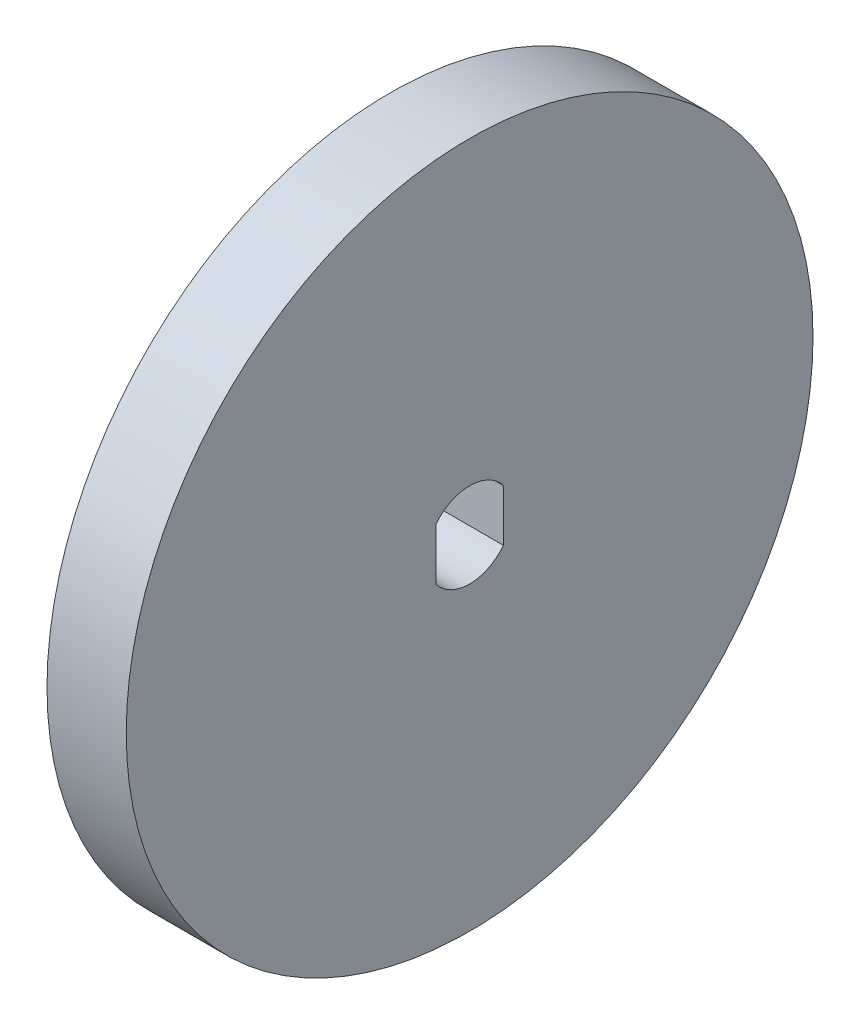
SolidWorks part; units mm, degrees
ref_plane "Front Plane" through (0, 0, 0) normal (0, 0, 1) x (1, 0, 0)
ref_plane "Top Plane" through (0, 0, 0) normal (0, 1, 0) x (1, 0, 0)
ref_plane "Right Plane" through (0, 0, 0) normal (1, 0, 0) x (0, 0, -1)
sketch "Sketch1" plane through (0, 0, 0) normal (1, 0, 0) x (0, 0, -1)
  line L0 (1.15, 0.8832) -> (1.15, -0.8832)
  line L1 (-1.15, 0.8832) -> (-1.15, -0.8832)
  line L2 (-1.15, 0) -> (1.15, 0) construction
  circle A0 centre (0, 0) radius 11.7
  arc A1 (1.15, 0.8832) -> (-1.15, 0.8832) centre (0, 0) ccw
  arc A2 (-1.15, -0.8832) -> (1.15, -0.8832) centre (0, 0) ccw
  dimension "D1" = 23.4
  dimension "D2" = 2.9
  dimension "D3" = 2.3
extrude "Base" add sketch "Sketch1" along normal blind 2.7
